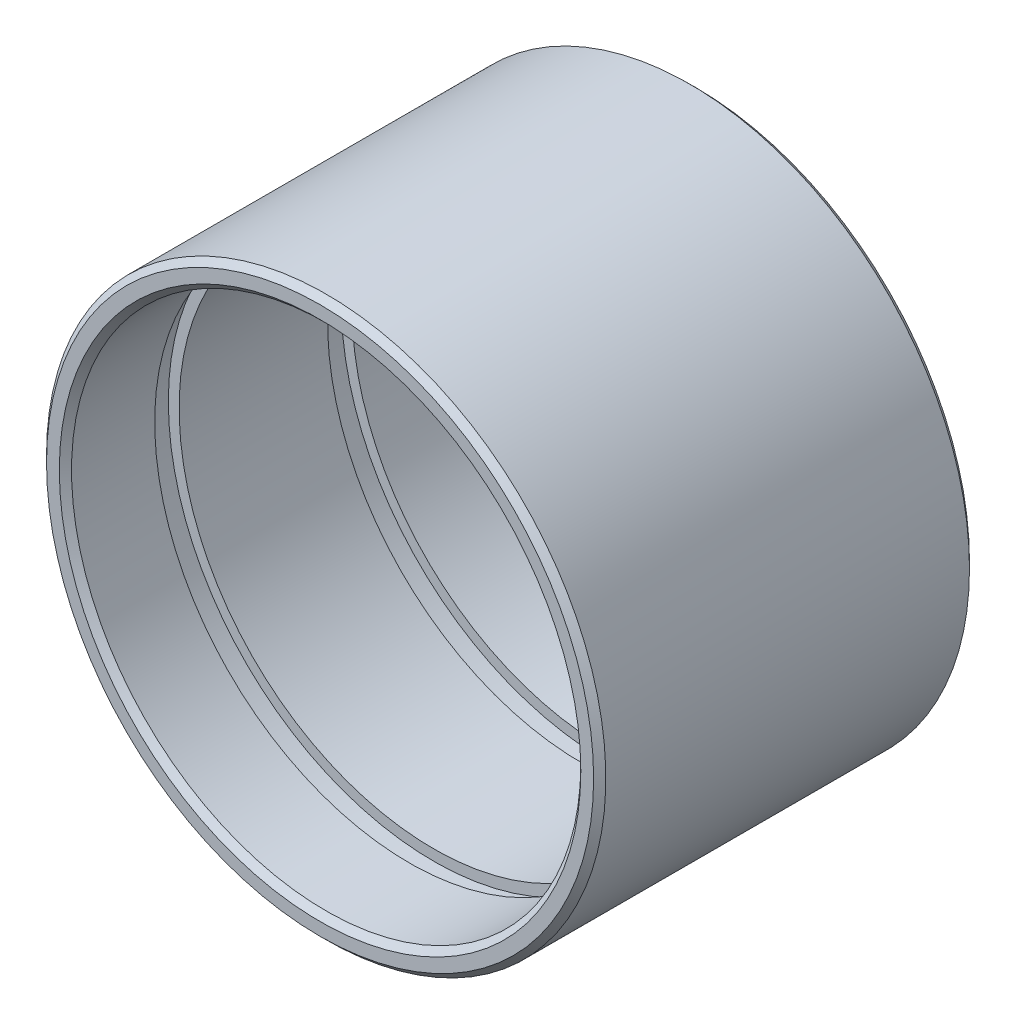
SolidWorks part; units mm, degrees
material "Tungsten"
ref_plane "Front" through (0, 0, 0) normal (0, 0, 1) x (1, 0, 0)
ref_plane "Top" through (0, 0, 0) normal (0, 1, 0) x (1, 0, 0)
ref_plane "Right" through (0, 0, 0) normal (1, 0, 0) x (0, 0, -1)
sketch "Sketch1" plane through (0, 0, 0) normal (0, 0, 1) x (1, 0, 0)
  circle A0 centre (0, 0) radius 17.4625
  circle A1 centre (0, 0) radius 15.9004
  dimension "D1" = 31.8008
  dimension "D2" = 34.925
extrude "Base-Extrude" add sketch "Sketch1" along normal blind 23.4696
ref_plane "Plane4" through (0, 0, 7.0993) normal (0, 0, 1) x (1, 0, 0)
sketch "Sketch2" plane through (0, 0, 7.0993) normal (0, 0, 1) x (1, 0, 0)
  circle A0 centre (0, 0) radius 16.5735
  dimension "D1" = 33.147
extrude "Cut-Extrude1" cut sketch "Sketch2" against normal blind 1.524
ref_plane "Plane5" through (0, 0, 16.3703) normal (0, 0, 1) x (1, 0, 0)
sketch "Sketch3" plane through (0, 0, 16.3703) normal (0, 0, 1) x (1, 0, 0)
  circle A0 centre (0, 0) radius 16.5735
  dimension "D1" = 33.147
extrude "Cut-Extrude2" cut sketch "Sketch3" along normal blind 1.524
chamfer "Chamfer1" distance 0.381 angle 45 4 edges at (17.4625, 0, 0) (17.4625, 0, 23.4696) (15.9004, 0, 0) (15.9004, 0, 23.4696)
